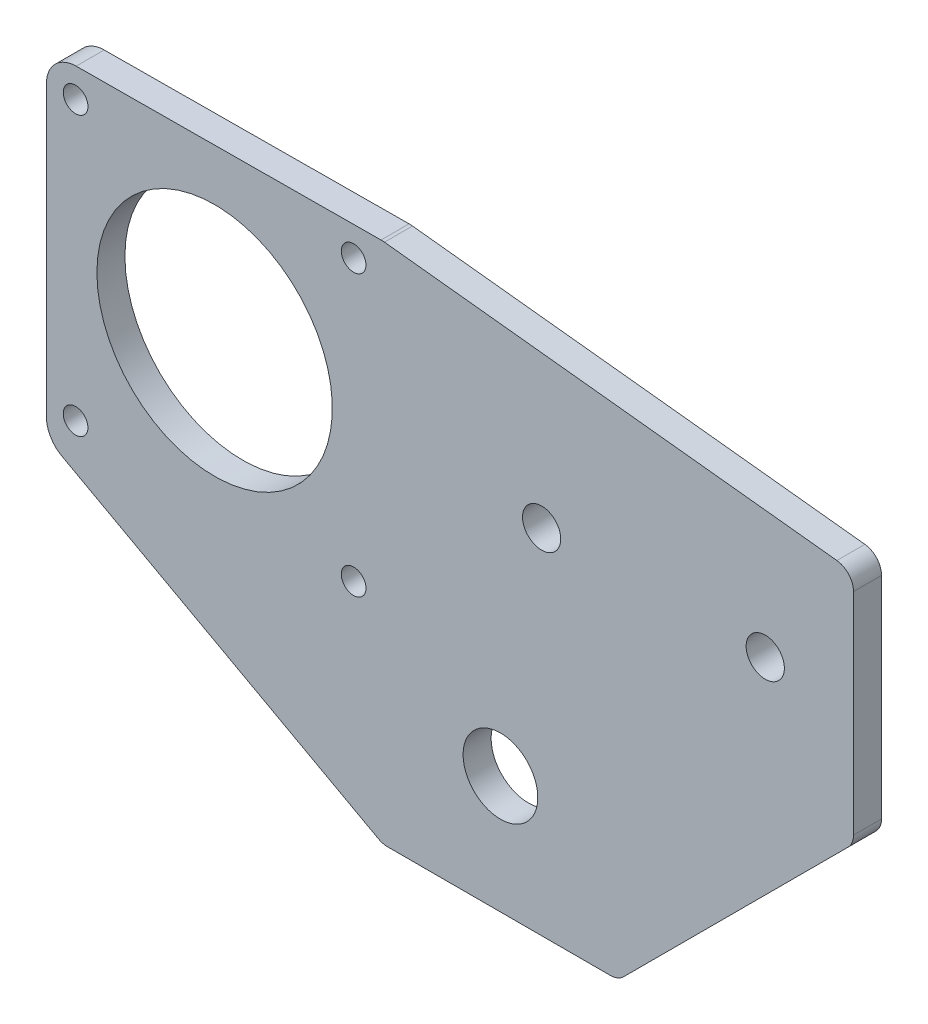
SolidWorks part; units mm, degrees
ref_plane "Front Plane" through (0, 0, 0) normal (0, 0, 1) x (1, 0, 0)
ref_plane "Top Plane" through (0, 0, 0) normal (0, 1, 0) x (1, 0, 0)
ref_plane "Right Plane" through (0, 0, 0) normal (1, 0, 0) x (0, 0, -1)
ref_plane "Plane1" through (-195.0896, 211.7105, -623.9496) normal (0.0087, 1, 0) x (1, -0.0087, 0)
sketch "Sketch3" plane through (0, 0, -194.1776) normal (0, 0, 1) x (1, 0, 0)
  line L1 (-209.5722, 79.1051) -> (-129.5722, 70.3551)
  line L2 (-209.5722, -9.6449) -> (-169.5722, -9.6449)
  line L8 (-169.5722, -9.6449) -> (-129.5722, 30.3551)
  line L11 (-266.7212, 78.7551) -> (-209.5722, 79.1051)
  line L12 (-266.7212, 78.7551) -> (-266.7212, 21.6051)
  line L18 (-129.5722, 30.3551) -> (-129.5722, 70.3551)
  line L21 (-266.7212, 21.6051) -> (-209.5722, -9.6449)
  circle A0 centre (-261.7712, 26.5551) radius 3
  circle A1 centre (-189.5722, 10.3551) radius 6.35
  circle A2 centre (-214.5222, 26.5551) radius 3
  circle A3 centre (-214.5222, 74.1247) radius 3
  circle A4 centre (-261.7712, 73.8353) radius 3
  circle A5 centre (-182.5722, 50.3551) radius 3.25
  circle A6 centre (-144.5722, 50.3551) radius 3.25
  circle A7 centre (-238.1462, 50.1801) radius 19.5
  circle A8 centre (-238.1462, 50.1801) radius 20.0056
  dimension "D3" = 40
  dimension "D27" = 6.5
  dimension "D28" = 6.5
  dimension "D1" = 8.75
  dimension "D4" = 38
  dimension "D5" = 57.15
  dimension "D6" = 15
  dimension "D7" = 8.75
  dimension "D8" = 40
  dimension "D9" = 20
  dimension "D10" = 57.15
  dimension "D11" = 40
  dimension "D12" = 80
  dimension "D13" = 28.575
  dimension "D14" = 40
  dimension "D15" = 20
  dimension "D16" = 4.95
  dimension "D17" = 4.95
  dimension "D18" = 4.95
  dimension "D19" = 4.95
  dimension "D20" = 4.95
  dimension "D21" = 4.95
  dimension "D22" = 4.95
  dimension "D23" = 4.95
  dimension "D24" = 20
  dimension "D25" = 20
  dimension "D26" = 28.575
extrude "Boss-Extrude1" add sketch "Sketch3" along normal blind 4.7625
fillet "Fillet1" radius 3.175 4 edges at (-129.5722, 70.3551, -191.7964) (-129.5722, 30.3551, -191.7964) (-169.5722, -9.6449, -191.7964) (-209.5722, -9.6449, -191.7964)
fillet "Fillet2" radius 5.08 3 edges at (-209.5722, 79.1051, -191.7964) (-266.7212, 78.7551, -191.7964) (-266.7212, 21.6051, -191.7964)
hole_wizard "M5 Tapped Hole1" positions "Sketch10" profile "Sketch9" tap size "M5" standard "ISO"
sketch "Sketch10" plane through (0, 0, -189.4151) normal (0, 0, 1) x (1, 0, 0)
  point P0 (-214.5222, 74.1247)
  point P3 (-261.7712, 73.8353)
  point P6 (-214.5222, 26.5551)
  point P9 (-261.7712, 26.5551)
sketch "Sketch9" plane through (-214.5222, 74.1247, -189.4151) normal (1, 0, 0) x (0, -1, 0)
  line L0 (0, 0) -> (0, 15.2618)
  line L1 (0, 15.2618) -> (2.1, 14)
  line L2 (2.1, 14) -> (2.1, 0)
  line L5 (2.1, 0) -> (0, 0)
  line L10 (0, 15.2618) -> (-2.1, 14) construction
  line L11 (0, -6.35) -> (0, 107.95) construction
  dimension "Tap Drill Dia." = 4.2
  dimension "Tap Drill Depth" = 14
  dimension "Drill Angle" = 118
cosmetic thread "Hole Thread1" parameters "D1"=4.7625, "D2"=5
cosmetic thread "Hole Thread2" parameters "D1"=4.7625, "D2"=5
cosmetic thread "Hole Thread3" parameters "D1"=4.7625, "D2"=5
cosmetic thread "Hole Thread4" parameters "D1"=4.7625, "D2"=5
